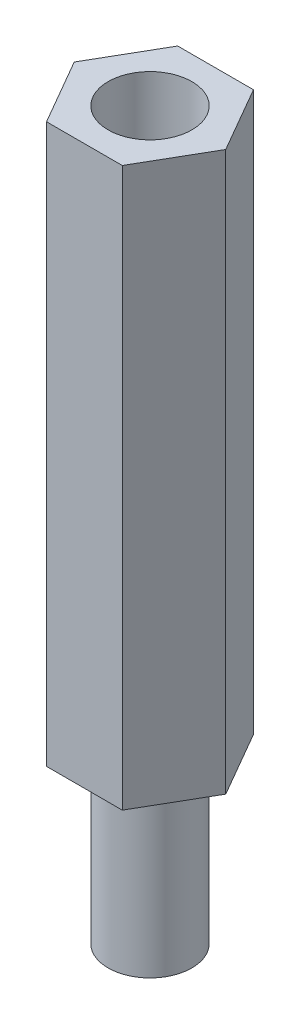
SolidWorks part; units mm, degrees
ref_plane "前视基准面" through (0, 0, 0) normal (0, 0, 1) x (1, 0, 0)
ref_plane "上视基准面" through (0, 0, 0) normal (0, 1, 0) x (1, 0, 0)
ref_plane "右视基准面" through (0, 0, 0) normal (1, 0, 0) x (0, 0, -1)
sketch "草图1" plane through (0, 0, 0) normal (0, 1, 0) x (1, 0, 0)
  line L1 (2.7135, 0) -> (1.3568, 2.35)
  line L2 (1.3568, 2.35) -> (-1.3568, 2.35)
  line L3 (-1.3568, 2.35) -> (-2.7135, 0)
  line L4 (-2.7135, 0) -> (-1.3568, -2.35)
  line L5 (-1.3568, -2.35) -> (1.3568, -2.35)
  line L6 (1.3568, -2.35) -> (2.7135, 0)
  circle A0 centre (0, 0) radius 2.35 construction
  circle A1 centre (0, 0) radius 1.5
extrude "凸台-拉伸1" add sketch "草图1" along normal blind 20
sketch "Sketch1" plane through (0, 0, 0) normal (0, -1, 0) x (1, 0, 0)
  circle A0 centre (0, 0) radius 1.5
extrude "Boss-Extrude1" add sketch "Sketch1" along normal blind 6 separate body
